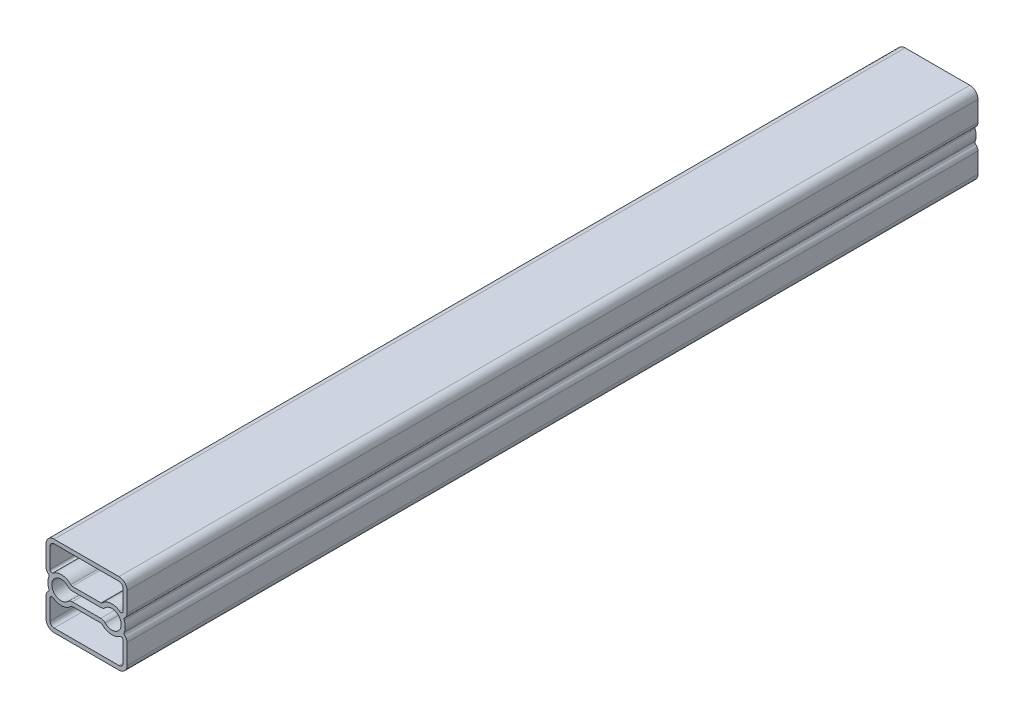
SolidWorks part; units mm, degrees
ref_plane "Front Plane" through (0, 0, 0) normal (0, 0, 1) x (1, 0, 0)
ref_plane "Top Plane" through (0, 0, 0) normal (0, 1, 0) x (1, 0, 0)
ref_plane "Right Plane" through (0, 0, 0) normal (1, 0, 0) x (0, 0, -1)
sketch "Sketch1" plane through (0, 0, 0) normal (0, 0, 1) x (1, 0, 0)
  line L0 (4.4671, -1.4668) -> (-4.4671, -1.4668)
  line L1 (-4.4671, 1.4668) -> (4.4671, 1.4668)
  line L2 (12.7, 3.9048) -> (12.7, 10.16)
  line L3 (10.16, 12.7) -> (-10.16, 12.7)
  line L4 (-12.7, 10.16) -> (-12.7, 3.9048)
  line L5 (-12.7, -3.9048) -> (-12.7, -10.16)
  line L6 (-10.16, -12.7) -> (10.16, -12.7)
  line L7 (12.7, -10.16) -> (12.7, -3.9048)
  line L8 (11.43, 10.16) -> (11.43, 3.9048)
  line L9 (4.4671, 2.7368) -> (-4.4671, 2.7368)
  line L10 (-11.43, 3.9048) -> (-11.43, 10.16)
  line L11 (-10.16, 11.43) -> (10.16, 11.43)
  line L12 (11.43, -3.9048) -> (11.43, -10.16)
  line L13 (10.16, -11.43) -> (-10.16, -11.43)
  line L14 (-11.43, -10.16) -> (-11.43, -3.9048)
  line L15 (-4.4671, -2.7368) -> (4.4671, -2.7368)
  arc A0 (5.8334, -2.0443) -> (4.4671, -1.4668) centre (4.4671, -3.3718) ccw
  arc A1 (-4.4671, -1.4668) -> (-5.8334, -2.0443) centre (-4.4671, -3.3718) ccw
  arc A2 (-5.8334, -2.0443) -> (-5.8334, 2.0443) centre (-7.9375, 0) cw
  arc A3 (-5.8334, 2.0443) -> (-4.4671, 1.4668) centre (-4.4671, 3.3718) ccw
  arc A4 (4.4671, 1.4668) -> (5.8334, 2.0443) centre (4.4671, 3.3718) ccw
  arc A5 (5.8334, 2.0443) -> (5.8334, -2.0443) centre (7.9375, 0) cw
  arc A6 (11.9832, 2.4158) -> (12.7, 3.9048) centre (10.795, 3.9048) ccw
  arc A7 (12.7, 10.16) -> (10.16, 12.7) centre (10.16, 10.16) ccw
  arc A8 (-10.16, 12.7) -> (-12.7, 10.16) centre (-10.16, 10.16) ccw
  arc A9 (-12.7, 3.9048) -> (-11.9832, 2.4158) centre (-10.795, 3.9048) ccw
  arc A10 (-11.9832, 2.4158) -> (-11.7963, 1.6675) centre (-12.3792, 1.9194) cw
  arc A11 (-11.7963, 1.6675) -> (-11.7963, -1.6675) centre (-7.9375, 0) ccw
  arc A12 (-11.7963, -1.6675) -> (-11.9832, -2.4158) centre (-12.3792, -1.9194) cw
  arc A13 (-11.9832, -2.4158) -> (-12.7, -3.9048) centre (-10.795, -3.9048) ccw
  arc A14 (-12.7, -10.16) -> (-10.16, -12.7) centre (-10.16, -10.16) ccw
  arc A15 (10.16, -12.7) -> (12.7, -10.16) centre (10.16, -10.16) ccw
  arc A16 (12.7, -3.9048) -> (11.9832, -2.4158) centre (10.795, -3.9048) ccw
  arc A17 (11.9832, -2.4158) -> (11.7963, -1.6675) centre (12.3792, -1.9194) cw
  arc A18 (11.7963, -1.6675) -> (11.7963, 1.6675) centre (7.9375, 0) ccw
  arc A19 (11.7963, 1.6675) -> (11.9832, 2.4158) centre (12.3792, 1.9194) cw
  arc A20 (10.16, 11.43) -> (11.43, 10.16) centre (10.16, 10.16) cw
  arc A21 (11.43, 3.9048) -> (10.42, 3.3924) centre (10.795, 3.9048) cw
  arc A22 (10.42, 3.3924) -> (4.9225, 2.9293) centre (7.9375, 0) ccw
  arc A23 (4.9225, 2.9293) -> (4.4671, 2.7368) centre (4.4671, 3.3718) cw
  arc A24 (-4.4671, 2.7368) -> (-4.9225, 2.9293) centre (-4.4671, 3.3718) cw
  arc A25 (-4.9225, 2.9293) -> (-10.42, 3.3924) centre (-7.9375, 0) ccw
  arc A26 (-10.42, 3.3924) -> (-11.43, 3.9048) centre (-10.795, 3.9048) cw
  arc A27 (-11.43, 10.16) -> (-10.16, 11.43) centre (-10.16, 10.16) cw
  arc A28 (4.4671, -2.7368) -> (4.9225, -2.9293) centre (4.4671, -3.3718) cw
  arc A29 (4.9225, -2.9293) -> (10.42, -3.3924) centre (7.9375, 0) ccw
  arc A30 (10.42, -3.3924) -> (11.43, -3.9048) centre (10.795, -3.9048) cw
  arc A31 (11.43, -10.16) -> (10.16, -11.43) centre (10.16, -10.16) cw
  arc A32 (-10.16, -11.43) -> (-11.43, -10.16) centre (-10.16, -10.16) cw
  arc A33 (-11.43, -3.9048) -> (-10.42, -3.3924) centre (-10.795, -3.9048) cw
  arc A34 (-10.42, -3.3924) -> (-4.9225, -2.9293) centre (-7.9375, 0) ccw
  arc A35 (-4.9225, -2.9293) -> (-4.4671, -2.7368) centre (-4.4671, -3.3718) cw
extrude "Boss-Extrude1" add sketch "Sketch1" against normal blind 266.7
